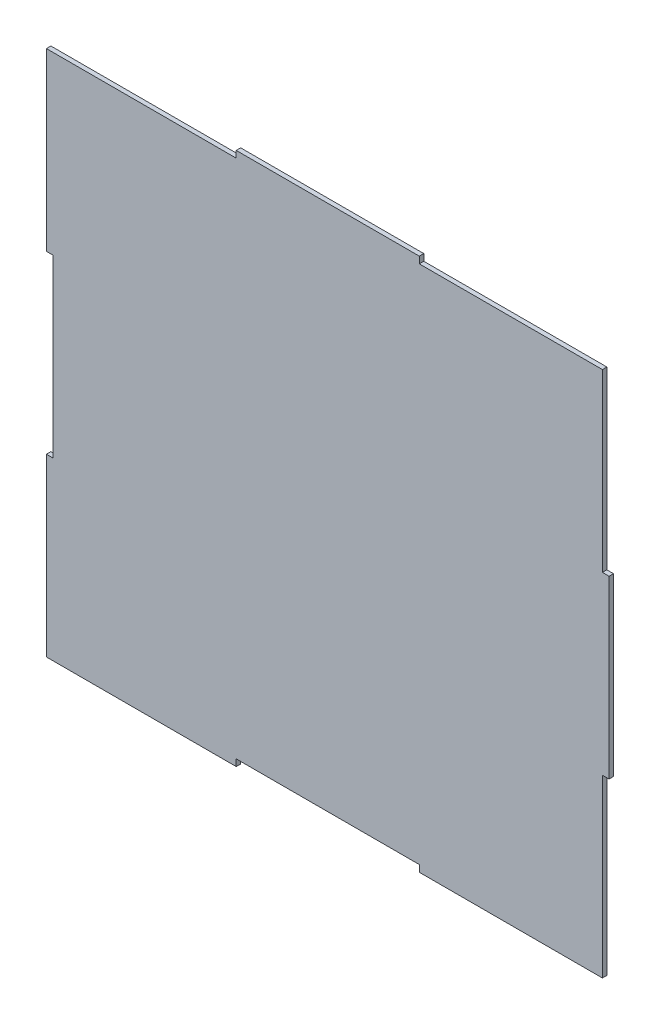
SolidWorks part; units mm, degrees
ref_plane "Front Plane" through (0, 0, 0) normal (0, 0, 1) x (1, 0, 0)
ref_plane "Top Plane" through (0, 0, 0) normal (0, 1, 0) x (1, 0, 0)
ref_plane "Right Plane" through (0, 0, 0) normal (1, 0, 0) x (0, 0, -1)
sketch "Sketch1" plane through (0, 0, 0) normal (0, 0, 1) x (1, 0, 0)
  line L0 (41, -118) -> (123, -118)
  line L1 (-123, -118) -> (-41, -118)
  line L2 (-123, -39.3333) -> (-123, 39.3333)
  line L3 (-123, 118) -> (-41, 118)
  line L4 (123, -118) -> (123, -39.3333)
  line L5 (-123, -118) -> (123, 118) construction
  line L6 (-123, 118) -> (123, -118) construction
  line L7 (-123, 118) -> (-126, 118)
  line L8 (123, 39.3333) -> (123, 118)
  line L9 (-41, -118) -> (-41, -115)
  line L10 (-41, -115) -> (41, -115)
  line L11 (41, -118) -> (41, -115)
  line L12 (123, -39.3333) -> (126, -39.3333)
  line L13 (41, 118) -> (123, 118)
  line L14 (123, 39.3333) -> (126, 39.3333)
  line L15 (126, -39.3333) -> (126, 39.3333)
  line L17 (-123, 39.3333) -> (-126, 39.3333)
  line L18 (-126, 118) -> (-126, 39.3333)
  line L19 (-123, -118) -> (-126, -118)
  line L21 (-123, -39.3333) -> (-126, -39.3333)
  line L22 (-126, -118) -> (-126, -39.3333)
  line L24 (-41, 118) -> (-41, 121)
  line L25 (-41, 121) -> (41, 121)
  line L26 (41, 118) -> (41, 121)
  dimension "D1" = 236
  dimension "D2" = 246
  dimension "D3" = 3
extrude "Boss-Extrude1" add sketch "Sketch1" along normal blind 2
equation "\"Resolution Projector X\"= 1920"
equation "\"Resolution Projector Y\"= 1080"
equation "\"Resolution Build\"= 0.1"
equation "\"Size Build Volume X\"= \"Resolution Projector X\" * \"Resolution Build\""
equation "\"Size Build Volume Y\"= 2 * \"Resolution Projector Y\" * \"Resolution Build\""
equation "\"Size Build Volume Z\"= \"Size Build Volume Y\""
equation "\"Thick\"= 0.125in"
equation "\"Size Enclosure Internal X\"= 350mm"
equation "\"Size Enclosure Internal Y\"= \"Size Enclosure Internal X\""
equation "\"Size Enclosure Internal Z\"= \"Size Enclosure Internal X\""
equation "\"Size Enclosure External Z\"= 1000mm"
equation "\"Diameter Screw\"= 3mm"
equation "\"Diameter Nut\"= 5.5mm"
equation "\"Thick Nut\"= 2.5mm"
equation "\"Length Screw\"= 12mm"
equation "\"D1@Sketch1\"=\"Size Build Volume Z\" + 20"
equation "\"D2@Sketch1\"=\"Size Build Volume Y\" + 30"
